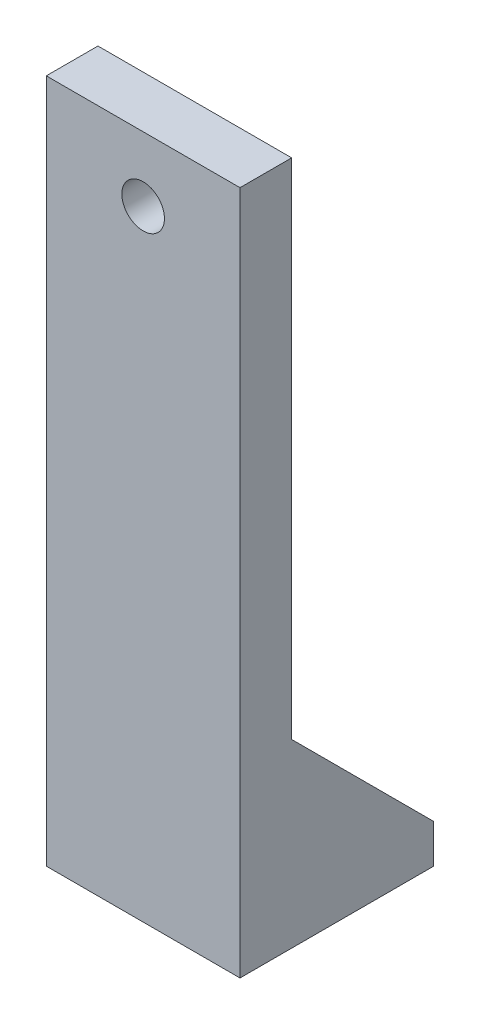
SolidWorks part; units mm, degrees
ref_plane "Front Plane" through (0, 0, 0) normal (0, 0, 1) x (1, 0, 0)
ref_plane "Top Plane" through (0, 0, 0) normal (0, 1, 0) x (1, 0, 0)
ref_plane "Right Plane" through (0, 0, 0) normal (1, 0, 0) x (0, 0, -1)
sketch "Sketch1" plane through (0, 0, 0) normal (0, 1, 0) x (1, 0, 0)
  line L1 (0, 0) -> (15, 0)
  line L2 (0, 0) -> (0, 15)
  line L3 (0, 15) -> (15, 15)
  line L4 (15, 0) -> (15, 15)
  circle A0 centre (7.5, 9) radius 2.65
  dimension "D3" = 5.3
  dimension "D1" = 15
  dimension "D2" = 15
  dimension "D4" = 6
  dimension "D5" = 7.5
extrude "Boss-Extrude1" add sketch "Sketch1" along normal blind 3
sketch "Sketch2" plane through (0, 3, 0) normal (0, 1, 0) x (1, 0, 0)
  line L0 (15, 0) -> (15, 15) construction
  line L1 (0, 0) -> (15, 0)
  line L2 (0, 0) -> (0, 4)
  line L3 (0, 4) -> (15, 4)
  line L4 (15, 0) -> (15, 4)
  dimension "D1" = 4
extrude "Boss-Extrude2" add sketch "Sketch2" along normal blind 50
sketch "Sketch3" plane through (15, 0, 0) normal (1, 0, 0) x (0, 0, -1)
  line L0 (4, 14) -> (15, 3)
  line L1 (4, 53) -> (4, 3) construction
  line L2 (15, 3) -> (4, 3)
  line L3 (4, 3) -> (4, 14)
  dimension "D1" = 45
extrude "Boss-Extrude3" add sketch "Sketch3" against normal blind 3
ref_plane "Plane1" through (7.5, 0, 0) normal (-1, 0, 0) x (0, 0, 1)
mirror "Mirror1" about plane through (7.5, 0, 0) normal (-1, 0, 0) of "Boss-Extrude3"
sketch "Sketch4" plane through (0, 0, -4) normal (0, 0, -1) x (-1, 0, 0)
  line L0 (0, 53) -> (0, 14) construction
  line L2 (-15, 53) -> (0, 53) construction
  circle A0 centre (-7.5, 48) radius 1.65
  dimension "D2" = 3.3
  dimension "D5" = 5
  dimension "D3" = 7.5
extrude "Cut-Extrude1" cut sketch "Sketch4" against normal blind 13
